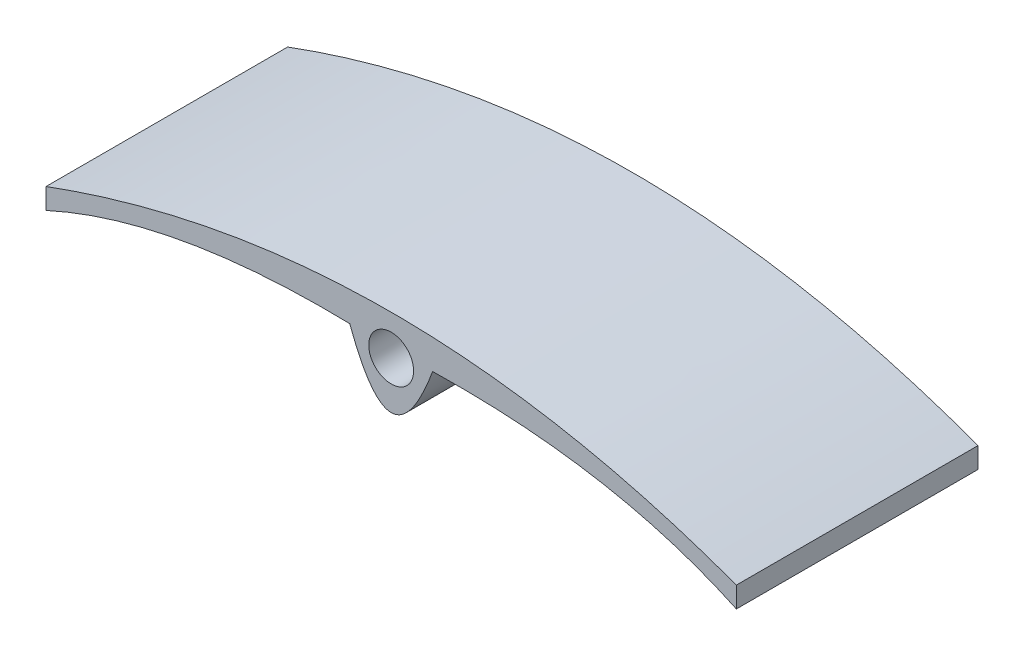
SolidWorks part; units mm, degrees
ref_plane "Front Plane" through (0, 0, 0) normal (0, 0, 1) x (1, 0, 0)
ref_plane "Top Plane" through (0, 0, 0) normal (0, 1, 0) x (1, 0, 0)
ref_plane "Right Plane" through (0, 0, 0) normal (1, 0, 0) x (0, 0, -1)
sketch "草圖1" plane through (0, 0, 0) normal (0, 0, 1) x (1, 0, 0)
  line L0 (-50, -3.4806) -> (0, 15) construction
  line L1 (0, 15) -> (50, -3.4806) construction
  line L2 (-50, -3.4806) -> (-50, -6.4806)
  line L3 (50, -3.4806) -> (50, -6.4806)
  line L4 (-6, 1.3143) -> (0, -15) construction
  line L5 (0, -15) -> (6, 1.3143) construction
  line L6 (6, 1.3143) -> (32.2287, 1.9206) construction
  line L7 (32.2287, 1.9206) -> (50, -6.4806) construction
  line L8 (-6, 1.3143) -> (-31.608, 1.9206) construction
  line L9 (-31.608, 1.9206) -> (-50, -6.4806) construction
  circle A0 centre (0, 0) radius 3.25
  spline S0 degree 2 poles (-50, -3.4806) (0, 15) (50, -3.4806) knots 0 0 0 1 1 1
  spline S1 degree 2 poles (-6, 1.3143) (0, -15) (6, 1.3143) knots 0 0 0 1 1 1
  spline S2 degree 2 poles (6, 1.3143) (32.2287, 1.9206) (50, -6.4806) knots 0 0 0 1 1 1
  spline S3 degree 2 poles (-6, 1.3143) (-31.608, 1.9206) (-50, -6.4806) knots 0 0 0 1 1 1
  dimension "D1" = 6.5
  dimension "D2" = 100
  dimension "D3" = 50
  dimension "D4" = 15
  dimension "D5" = 3
  dimension "D6" = 15
  dimension "D7" = 6
  dimension "D8" = 6
  dimension "D9" = 32.2287
  dimension "D10" = 31.608
extrude "填料-伸長1" add sketch "草圖1" along normal blind 35
